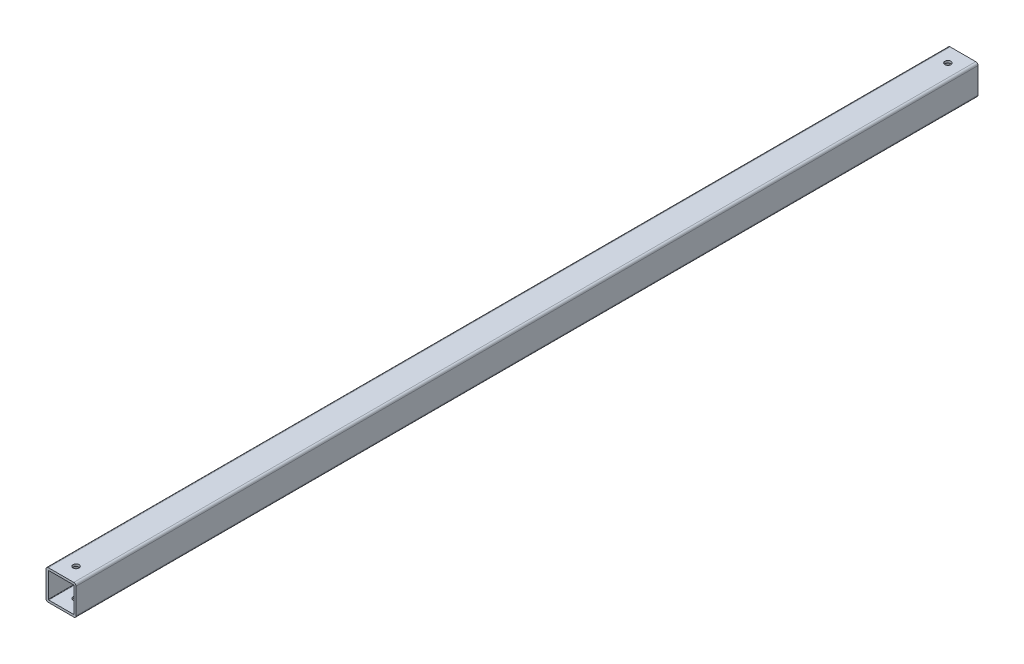
SolidWorks part; units mm, degrees
ref_plane "Front Plane" through (0, 0, 0) normal (0, 0, 1) x (1, 0, 0)
ref_plane "Top Plane" through (0, 0, 0) normal (0, 1, 0) x (1, 0, 0)
ref_plane "Right Plane" through (0, 0, 0) normal (1, 0, 0) x (0, 0, -1)
sketch "Sketch1" plane through (0, 0, 0) normal (0, 0, 1) x (1, 0, 0)
  line L1 (-20, 20) -> (20, 20)
  line L2 (-20, 20) -> (-20, -20)
  line L3 (-20, -20) -> (20, -20)
  line L4 (20, 20) -> (20, -20)
  line L5 (-20, 20) -> (20, -20) construction
  line L6 (-20, -20) -> (20, 20) construction
  point P0 (0, 0)
  dimension "D1" = 40
  dimension "D2" = 40
extrude "Extrude-Thin1" add sketch "Sketch1" along normal blind 1200 thin
fillet "Fillet1" radius 0.5 4 edges at (-17, -17, 600) (-17, 17, 600) (17, 17, 600) (17, -17, 600)
fillet "Fillet2" radius 3 4 edges at (20, -20, 600) (-20, -20, 600) (20, 20, 600) (-20, 20, 600)
hole_wizard "Ø8.0 (8) Diameter Hole1" positions "Sketch4" profile "Sketch3" hole size "Ø8.0" standard "ANSI Metric" end condition through all
sketch "Sketch4" plane through (0, 20, 0) normal (0, 1, 0) x (1, 0, 0)
  line L2 (0, 0) -> (0, -1200) construction
  line L3 (17, -1200) -> (-17, -1200) construction
  line L5 (17, 0) -> (-17, 0) construction
  point P0 (0, -20)
  point P2 (0, -1180)
  dimension "D1" = 20
  dimension "D2" = 20
sketch "Sketch3" plane through (0, 20, 20) normal (1, 0, 0) x (0, 0, 1)
  line L0 (0, 0) -> (0, 40)
  line L1 (0, 40) -> (4, 40)
  line L2 (4, 40) -> (4, 0)
  line L5 (4, 0) -> (0, 0)
  line L11 (0, -6.35) -> (0, 107.95) construction
  dimension "Thru Hole Dia." = 8
  dimension "Thru Hole Depth" = 40
equation "\"a\"= \"Beam Profile@Plasma Beta.Assembly\""
equation "\"b\"= 3"
equation "\"L\"= \"Width@Plasma Beta.Assembly\""
equation "\"D2@Sketch1\"=\"a\""
equation "\"D1@Sketch1\"=\"a\""
equation "\"D1@Extrude-Thin1\"=\"L\""
equation "\"D5@Extrude-Thin1\"=\"b\""
equation "\"D1@Fillet2\"=\"b\""
